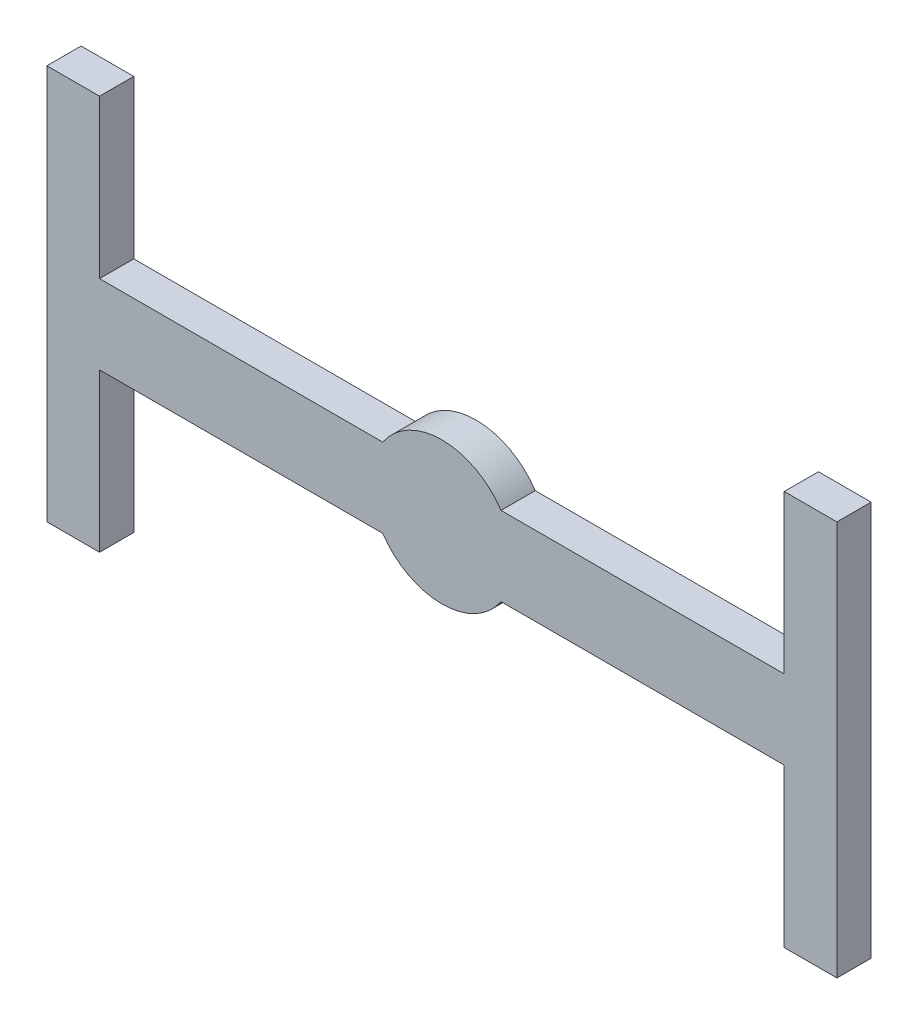
SolidWorks part; units mm, degrees
ref_plane "Plan de face" through (0, 0, 0) normal (0, 0, 1) x (1, 0, 0)
ref_plane "Plan de dessus" through (0, 0, 0) normal (0, 1, 0) x (1, 0, 0)
ref_plane "Plan de droite" through (0, 0, 0) normal (1, 0, 0) x (0, 0, -1)
sketch "Esquisse1" plane through (0, 0, 0) normal (0, 0, 1) x (1, 0, 0)
  line L1 (0, 0) -> (3000, 0)
  line L2 (0, 0) -> (0, 1500)
  line L3 (0, 1500) -> (3000, 1500)
  line L4 (3000, 0) -> (3000, 1500)
  dimension "D1" = 3000
  dimension "D2" = 1500
extrude "Boss.-Extru.1" add sketch "Esquisse1" against normal blind 130 contours L3 L4 L1 L2
sketch "Esquisse3" plane through (0, 0, 0) normal (0, 0, 1) x (1, 0, 0)
  line L0 (200, 1500) -> (200, 900)
  line L1 (0, 1500) -> (3000, 1500) construction
  line L2 (200, 900) -> (2800, 900)
  line L3 (2800, 900) -> (2800, 1500)
  line L4 (200, 1500) -> (2800, 1500)
  line L5 (0, 0) -> (0, 1500) construction
  line L6 (3000, 0) -> (3000, 1500) construction
  line L7 (200, 0) -> (200, 600)
  line L8 (0, 0) -> (3000, 0) construction
  line L9 (200, 600) -> (2800, 600)
  line L10 (2800, 600) -> (2800, 0)
  line L11 (200, 0) -> (2800, 0)
  dimension "D1" = 200
  dimension "D2" = 200
  dimension "D3" = 300
  dimension "D4" = 600
sketch "Esquisse4" plane through (0, 0, 0) normal (0, 0, 1) x (1, 0, 0)
  line L0 (200, 1500) -> (2800, 1500) construction
  line L1 (0, 0) -> (0, 1500) construction
  line L2 (200, 0) -> (200, 600) construction
  line L3 (200, 0) -> (2800, 0) construction
  line L4 (2800, 600) -> (2800, 0) construction
  line L5 (200, 600) -> (2800, 600) construction
  line L6 (200, 1500) -> (200, 900) construction
  line L7 (2800, 900) -> (2800, 1500) construction
  line L8 (200, 900) -> (2800, 900) construction
  line L9 (200, 0) -> (200, 600)
  line L10 (200, 0) -> (2800, 0)
  line L11 (2800, 600) -> (2800, 0)
  line L12 (200, 600) -> (1275.5006, 600)
  line L13 (200, 1500) -> (200, 900)
  line L14 (200, 1500) -> (2800, 1500)
  line L15 (2800, 900) -> (2800, 1500)
  line L16 (200, 900) -> (1275.5006, 900)
  line L17 (1724.4994, 900) -> (2800, 900)
  line L18 (1724.4994, 600) -> (2800, 600)
  circle A1 centre (1500, 750) radius 270
  line M3 (0, 0) -> (3000, 0)
  line M5 (3000, 1500) -> (0, 1500)
  dimension "D4" = 540
  dimension "D1" = 750
  dimension "D2" = 1500
extrude "Enlèv. mat.-Extru.1" cut sketch "Esquisse4" against normal blind 130 contours A1 L17 L15 L13 L16 M5 | A1 L12 L9 L11 L18 M3
